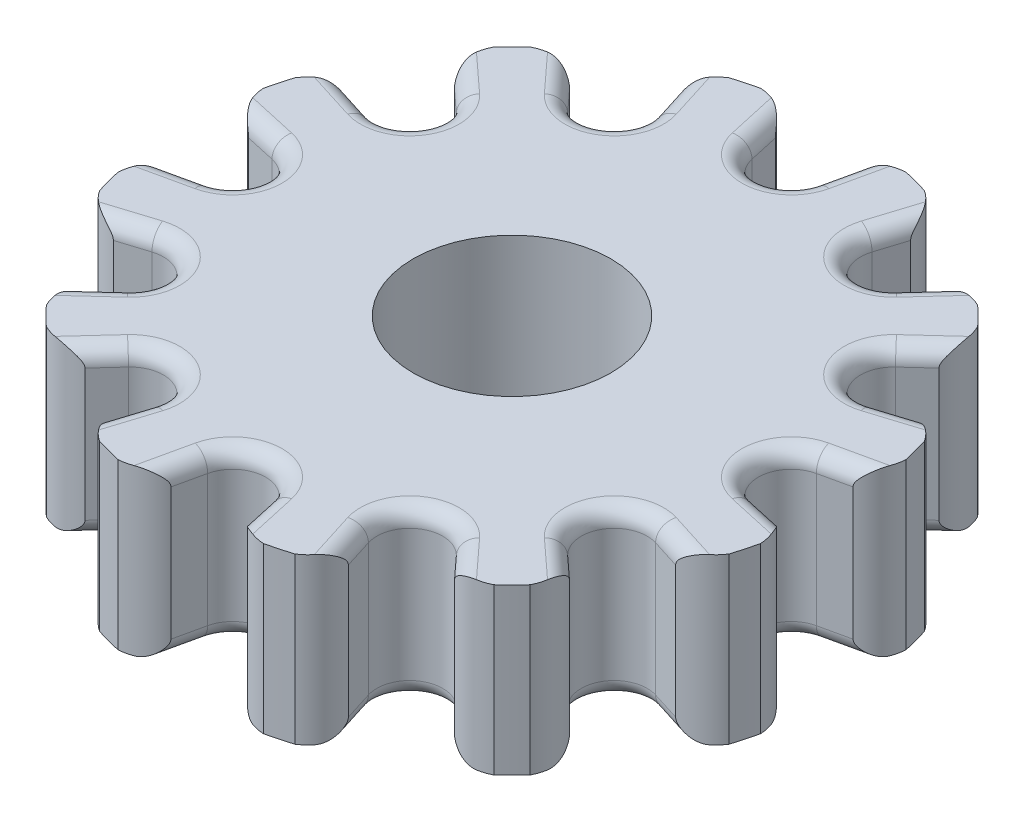
SolidWorks part; units mm, degrees
ref_plane "Front Plane" through (0, 0, 0) normal (0, 0, 1) x (1, 0, 0)
ref_plane "Top Plane" through (0, 0, 0) normal (0, 1, 0) x (1, 0, 0)
ref_plane "Right Plane" through (0, 0, 0) normal (1, 0, 0) x (0, 0, -1)
sketch "Sketch2" plane through (0, 0, 0) normal (0, 1, 0) x (1, 0, 0)
  circle A0 centre (0, 0) radius 20
  dimension "D1" = 40
extrude "Boss-Extrude2" add sketch "Sketch2" along normal mid plane 10
sketch "Sketch3" plane through (0, 5, 0) normal (0, 1, 0) x (1, 0, 0)
  line L1 (1.9525, 16.519) -> (2.685, 19.819)
  line L2 (0, 16.9523) -> (0, 0) construction
  line L4 (-1.9525, 16.519) -> (-2.685, 19.819)
  arc A0 (2.685, 19.819) -> (-2.685, 19.819) centre (0, 0) ccw
  arc A1 (-1.9525, 16.519) -> (1.9525, 16.519) centre (0, 16.9523) ccw
  circle A6 centre (0, 0) radius 20 construction
  dimension "D2" = 4
  dimension "D3" = 25.03
  dimension "D1" = 3.3
sketch "Sketch4" plane through (0, 5, 0) normal (0, 1, 0) x (1, 0, 0)
  circle A0 centre (0, 0) radius 6
  dimension "D1" = 12
extrude "Cut-Extrude3" cut sketch "Sketch4" against normal blind 10
extrude "Cut-Extrude5" cut sketch "Sketch3" against normal blind 10
fillet "Fillet1" radius 1 8 edges at (2.3187, -5, -18.169) (2.3187, 5, -18.169) (0, -5, -14.9523) (0, 5, -14.9523) (-2.685, 0, -19.819) (-2.3187, -5, -18.169) (-2.3187, 5, -18.169) (2.685, 0, -19.819)
pattern_circular "CirPattern3" count 12 over 360 about axis through (0, 0, 0) along (0, 1, 0) of "Cut-Extrude5", "Fillet1"
sketch "Sketch5" plane through (0, 0, 0) normal (0, 1, 0) x (1, 0, 0)
  line L0 (0, 0) -> (0, 16.519) construction
  line L1 (2.9287, 16.3023) -> (5.6148, 15.5825) construction
  line L2 (5.6148, 15.5825) -> (4.2718, 15.9424) construction
  line L4 (1.9525, 16.519) -> (6.5686, 15.2821) construction
  line L5 (1.9525, 16.519) -> (-1.9525, 16.519) construction
  line L6 (6.5686, 15.2821) -> (9.9504, 13.3296) construction
  line L7 (9.9504, 13.3296) -> (0, 0) construction
  arc A0 (1.9525, 16.519) -> (6.5686, 15.2821) centre (4.5292, 16.9031) cw
  arc A1 (6.5686, 15.2821) -> (1.9525, 16.519) centre (4.9339, 18.4137) ccw
  point P15 (0, 16.519)
  dimension "D1" = 2.6052
  dimension "D2" = 3.5326
extrude "Cut-Extrude6" cut sketch "Sketch5" against normal mid plane 10
pattern_circular "CirPattern4" count 12 over 360 about axis through (0, 0, 0) along (0, 1, 0) of "Cut-Extrude6"
